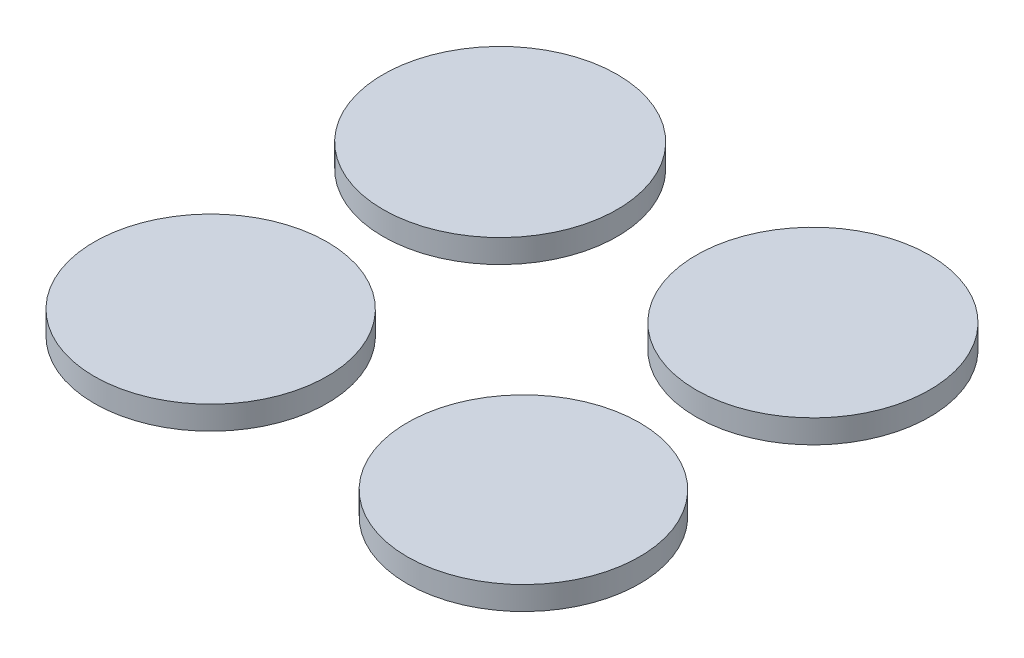
SolidWorks part; units mm, degrees
ref_plane "Front Plane" through (0, 0, 0) normal (0, 0, 1) x (1, 0, 0)
ref_plane "Top Plane" through (0, 0, 0) normal (0, 1, 0) x (1, 0, 0)
ref_plane "Right Plane" through (0, 0, 0) normal (1, 0, 0) x (0, 0, -1)
sketch "Sketch1" plane through (0, 0, 0) normal (0, 1, 0) x (1, 0, 0)
  circle A0 centre (0, 0) radius 20
  circle A1 centre (53.4357, 0) radius 19.95
  circle A2 centre (53.4357, -49.4625) radius 19.85
  circle A3 centre (0, -49.4625) radius 19.9
  point P9 (53.4357, -49.4625)
  dimension "D1" = 40
  dimension "D2" = 39.9
  dimension "D3" = 39.7
  dimension "D4" = 39.8
extrude "Boss-Extrude1" add sketch "Sketch1" along normal blind 4
